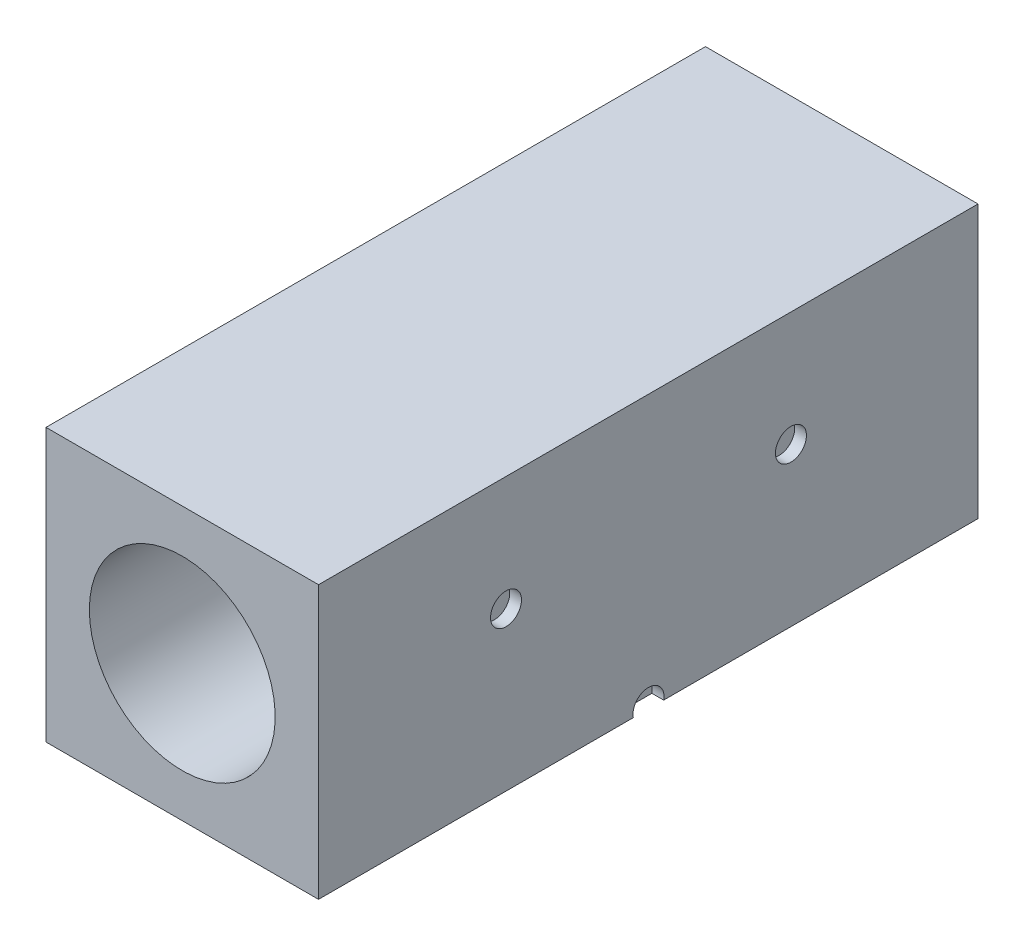
SolidWorks part; units mm, degrees
ref_plane "Front Plane" through (0, 0, 0) normal (0, 0, 1) x (1, 0, 0)
ref_plane "Top Plane" through (0, 0, 0) normal (0, 1, 0) x (1, 0, 0)
ref_plane "Right Plane" through (0, 0, 0) normal (1, 0, 0) x (0, 0, -1)
sketch "Sketch1" plane through (0, 0, 0) normal (0, 0, 1) x (1, 0, 0)
  line L1 (-22, -22) -> (22, -22)
  line L2 (-22, -22) -> (-22, 22)
  line L3 (-22, 22) -> (22, 22)
  line L4 (22, -22) -> (22, 22)
  line L5 (-22, -22) -> (22, 22) construction
  line L6 (-22, 22) -> (22, -22) construction
  point P0 (0, 0)
  dimension "D1" = 44
  dimension "D2" = 44
extrude "Boss-Extrude1" add sketch "Sketch1" along normal blind 106.47
sketch "Sketch5" plane through (0, 0, 0) normal (0, 0, -1) x (-1, 0, 0)
  circle A0 centre (0, 0) radius 15
extrude "Cut-Extrude2" cut sketch "Sketch5" against normal blind 106.47
sketch "Sketch8" plane through (0, 0, 0) normal (0, 0, -1) x (-1, 0, 0)
  line L0 (15, 0) -> (22, 0)
  line L1 (22, 22) -> (22, -22) construction
  circle A0 centre (0, 0) radius 15 construction
sketch "Sketch9" plane through (0, 22, 0) normal (0, 1, 0) x (1, 0, 0)
  line L0 (-22, -36.7) -> (22, -36.7)
  line L1 (-22, -106.47) -> (-22, 0) construction
  line L2 (22, -106.47) -> (22, 0) construction
  line L3 (22, 0) -> (-22, 0) construction
  line L4 (-22, -36.7) -> (22, -36.7)
  dimension "D1" = 36.7
sketch "Sketch10" plane through (-22, 0, 0) normal (-1, 0, 0) x (0, 0, 1)
  line L0 (0, 22) -> (0, -22) construction
  line L1 (106.47, 22) -> (0, 22) construction
  circle A0 centre (30.2, 3.5) radius 2.5
  circle A1 centre (76.2, 3.5) radius 2.5
  circle A2 centre (53.2, -21.4992) radius 2.5
  dimension "D1" = 30.2
  dimension "D3" = 46
  dimension "D4" = 33.97
  dimension "D5" = 33.97
  dimension "D2" = 18.5
extrude "Cut-Extrude9" cut sketch "Sketch10" against normal blind 1.9
mirror "Mirror1" about plane through (0, 0, 0) normal (1, 0, 0) of "Cut-Extrude9"
